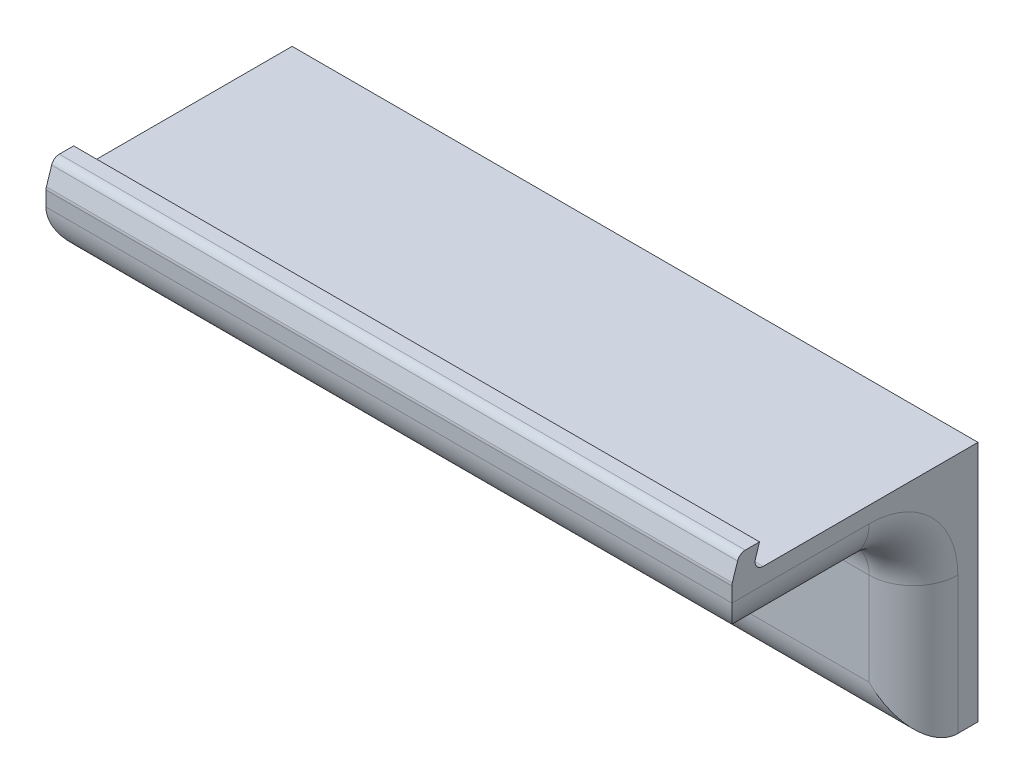
SolidWorks part; units mm, degrees
ref_plane "Front Plane" through (0, 0, 0) normal (0, 0, 1) x (1, 0, 0)
ref_plane "Top Plane" through (0, 0, 0) normal (0, 1, 0) x (1, 0, 0)
ref_plane "Right Plane" through (0, 0, 0) normal (1, 0, 0) x (0, 0, -1)
sketch "Sketch1" plane through (0, 0, 0) normal (0, 0, 1) x (1, 0, 0)
  line L1 (-42.5, -15) -> (42.5, -15)
  line L2 (-42.5, -15) -> (-42.5, 15)
  line L3 (-42.5, 15) -> (42.5, 15)
  line L4 (42.5, -15) -> (42.5, 15)
  line L5 (-42.5, -15) -> (42.5, 15) construction
  line L6 (-42.5, 15) -> (42.5, -15) construction
  point P0 (0, 0)
  dimension "D1" = 85
  dimension "D2" = 30
extrude "Boss-Extrude1" add sketch "Sketch1" along normal blind 8
sketch "Sketch2" plane through (0, 0, 8) normal (0, 0, 1) x (1, 0, 0)
  line L0 (42.5, -15) -> (42.5, 15) construction
  line L1 (-42.5, 15) -> (42.5, 15)
  line L2 (-42.5, 15) -> (-42.5, 7.5)
  line L3 (-42.5, 7.5) -> (42.5, 7.5)
  line L4 (42.5, 15) -> (42.5, 7.5)
  dimension "D1" = 7.5
extrude "Boss-Extrude2" add sketch "Sketch2" along normal blind 22.5
sketch "Sketch3" plane through (0, 0, 8) normal (0, 0, 1) x (1, 0, 0)
  line L0 (-42.5, 7.5) -> (-42.5, -15) construction
  line L1 (-42.5, -3.75) -> (42.5, -3.75)
  line L2 (42.5, -15) -> (42.5, 7.5) construction
  line L3 (-42.5, -3.75) -> (-22.5, -3.75)
  line L4 (42.5, -3.75) -> (22.5, -3.75)
  dimension "D1" = 20
  dimension "D2" = 20
hole_wizard "CSK for M3 Flat Head Machine Screw1" positions "Sketch4" profile "Sketch5" countersink size "M3" standard "ANSI Metric" end condition through all
sketch "Sketch4" plane through (0, 0, 8) normal (0, 0, 1) x (1, 0, 0)
  point P0 (-22.5, -3.75)
  point P3 (22.5, -3.75)
sketch "Sketch5" plane through (-22.5, -3.75, 8) normal (1, 0, 0) x (0, -1, 0)
  line L0 (0, 0) -> (0, 8)
  line L1 (0, 8) -> (1.7, 8)
  line L2 (1.7, 8) -> (1.7, 1.45)
  line L3 (1.7, 1.45) -> (3.15, 0)
  line L5 (3.15, 0) -> (0, 0)
  line L6 (-1.7, 1.45) -> (-3.15, 0) construction
  line L11 (0, -6.35) -> (0, 107.95) construction
  dimension "Thru Hole Dia." = 3.4
  dimension "Thru Hole Depth" = 8
  dimension "Near C'Sink Dia." = 6.3
  dimension "Near C'Sink Angle" = 90
sketch "Sketch7" plane through (-42.5, 0, 0) normal (-1, 0, 0) x (0, 0, 1)
  line L0 (30.5, 15) -> (29.5729, 17.8532)
  line L1 (30.5, 15) -> (0, 15) construction
  line L2 (28, 15) -> (27.0729, 17.8532)
  line L3 (27.0729, 17.8532) -> (29.5729, 17.8532)
  line L10 (0, 15) -> (0, -15)
  line L11 (0, -15) -> (8, -15)
  line L12 (8, -15) -> (8, 7.5)
  line L13 (8, 7.5) -> (30.5, 7.5)
  line L14 (30.5, 7.5) -> (30.5, 15)
  line L15 (30.5, 15) -> (0, 15)
  line L21 (30.5, 15) -> (28, 15)
  dimension "D1" = 108
  dimension "D2" = 108
  dimension "D3" = 2.5
  dimension "D4" = 3
  dimension "D5" = 0
extrude "Boss-Extrude3" add sketch "Sketch7" against normal up to surface (85 mm away) up to face at (42.5, 2.5, 12.8333)
fillet "Fillet1" radius 5.5 7 edges at (0, 7.5, 8) (42.5, 7.5, 19.25) (-42.5, -3.75, 8) (0, -15, 8) (42.5, -3.75, 8) (-42.5, 7.5, 19.25) (0, 7.5, 30.5)
fillet "Fillet2" radius 1 1 edges at (0, 15, 28)
fillet "Fillet3" radius 1 2 edges at (0, 17.8532, 29.5729) (0, 15, 30.5)
